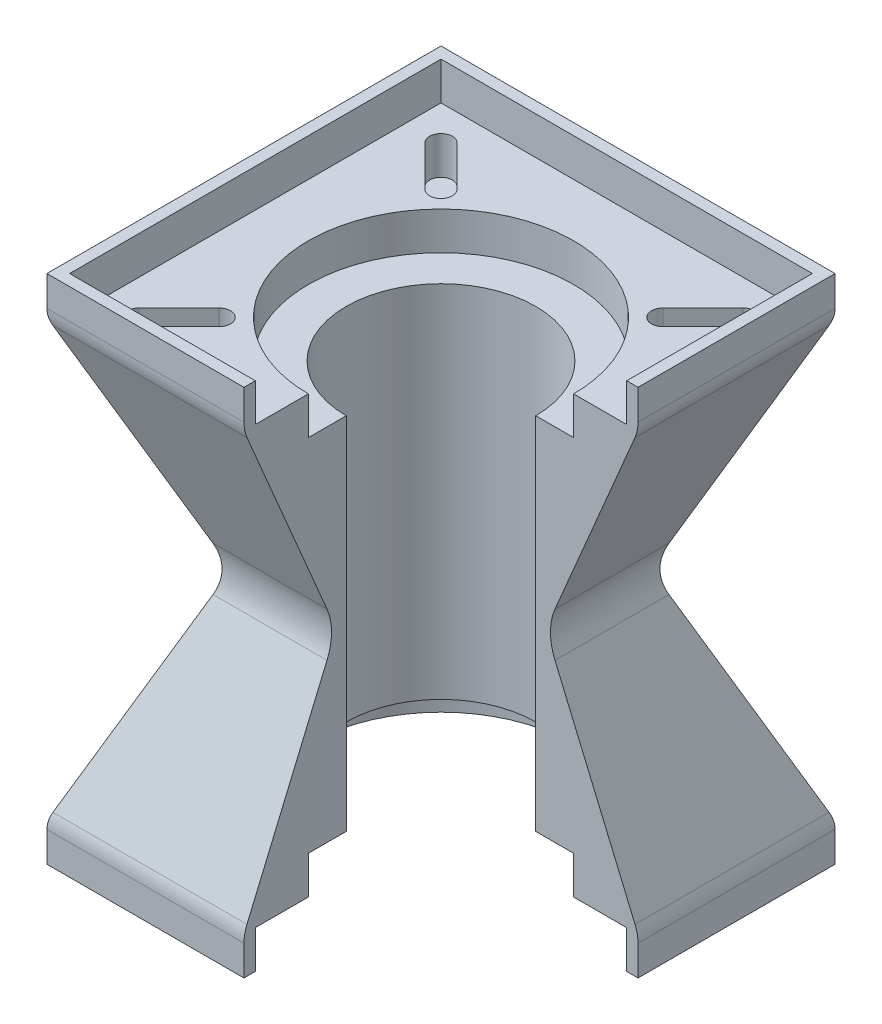
SolidWorks part; units mm, degrees
ref_plane "Front Plane" through (0, 0, 0) normal (0, 0, 1) x (1, 0, 0)
ref_plane "Top Plane" through (0, 0, 0) normal (0, 1, 0) x (1, 0, 0)
ref_plane "Right Plane" through (0, 0, 0) normal (1, 0, 0) x (0, 0, -1)
sketch "Sketch1" plane through (0, 0, 0) normal (0, 1, 0) x (1, 0, 0)
  line L1 (0, 0) -> (104, 0)
  line L2 (0, 0) -> (0, 104)
  line L3 (0, 104) -> (104, 104)
  line L4 (104, 0) -> (104, 104)
  dimension "D1" = 104
  dimension "D2" = 104
extrude "Boss-Extrude1" add sketch "Sketch1" along normal blind 115
sketch "Sketch2" plane through (0, 0, 0) normal (0, 0, 1) x (1, 0, 0)
  line L0 (0, 57.5) -> (104, 57.5) construction
  line L1 (0, 115) -> (0, 0) construction
  line L2 (104, 115) -> (104, 0) construction
  line L3 (104, 115) -> (79.5927, 57.5)
  line L4 (0, 115) -> (104, 115) construction
  line L5 (79.5927, 57.5) -> (104, 0)
  line L6 (0, 0) -> (104, 0) construction
  dimension "D1" = 23
extrude "Cut-Extrude1" cut sketch "Sketch2" against normal through all and the other way through all
sketch "Sketch3" plane through (0, 115, 0) normal (0, 1, 0) x (1, 0, 0)
  line L0 (0, 104) -> (104, 0) construction
  line L2 (0, 0) -> (104, 104) construction
  circle A0 centre (52, 52) radius 25
  dimension "D1" = 50
extrude "Cut-Extrude2" cut sketch "Sketch3" against normal through all
pattern_circular "CirPattern1" count 4 every 90 about axis through (52, 0, -52) along (0, 1, 0) of "Cut-Extrude2", "Cut-Extrude1"
sketch "Sketch4" plane through (0, 115, 0) normal (0, 1, 0) x (1, 0, 0)
  circle A0 centre (52, 52) radius 35
  dimension "D1" = 70
extrude "Cut-Extrude3" cut sketch "Sketch4" against normal blind 10
sketch "Sketch5" plane through (0, 0, 0) normal (0, -1, 0) x (1, 0, 0)
  circle A0 centre (52, -52) radius 35
  dimension "D1" = 70
extrude "Cut-Extrude4" cut sketch "Sketch5" against normal blind 10
fillet "Fillet2" radius 15 4 edges at (79.5927, 57.5, -52) (52, 57.5, -24.4073) (24.4073, 57.5, -52) (52, 57.5, -79.5927)
sketch "Sketch6" plane through (0, 115, 0) normal (0, 1, 0) x (1, 0, 0)
  line L4 (104, 104) -> (0, 104)
  line L5 (0, 104) -> (0, 0)
  line L6 (0, 0) -> (104, 0)
  line L7 (104, 0) -> (104, 104)
  line L8 (3, 101) -> (3, 3)
  line L9 (3, 3) -> (101, 3)
  line L10 (101, 3) -> (101, 101)
  line L11 (101, 101) -> (3, 101)
  line L12 (3, 101) -> (3, 3)
  line L13 (3, 3) -> (101, 3)
  line L14 (101, 3) -> (101, 101)
  line L15 (101, 101) -> (3, 101)
  dimension "D1" = 3
  dimension "D2" = 3
extrude "Boss-Extrude2" add sketch "Sketch6" along normal blind 10
sketch "Sketch7" plane through (0, 0, 0) normal (0, -1, 0) x (1, 0, 0)
  line L4 (104, 0) -> (0, 0)
  line L5 (0, 0) -> (0, -104)
  line L6 (0, -104) -> (104, -104)
  line L7 (104, -104) -> (104, 0)
  line L8 (3, -3) -> (3, -101)
  line L9 (3, -101) -> (101, -101)
  line L10 (101, -101) -> (101, -3)
  line L11 (101, -3) -> (3, -3)
  line L12 (3, -3) -> (3, -101)
  line L13 (3, -101) -> (101, -101)
  line L14 (101, -101) -> (101, -3)
  line L15 (101, -3) -> (3, -3)
  dimension "D1" = 3
  dimension "D2" = 3
extrude "Boss-Extrude3" add sketch "Sketch7" along normal blind 10
sketch "Sketch8" plane through (0, 0, 0) normal (0, -1, 0) x (1, 0, 0)
  line L0 (0, 0) -> (104, -104)
  line L1 (20.5337, -20.5337) -> (9.9271, -9.9271) construction
  line L4 (18.4124, -22.6551) -> (7.8058, -12.0485)
  line L5 (22.6551, -18.4124) -> (12.0485, -7.8058)
  line L6 (83.4663, -20.5337) -> (94.0729, -9.9271) construction
  line L7 (81.3449, -18.4124) -> (91.9515, -7.8058)
  line L8 (85.5876, -22.6551) -> (96.1942, -12.0485)
  line L9 (83.4663, -83.4663) -> (94.0729, -94.0729) construction
  line L10 (85.5876, -81.3449) -> (96.1942, -91.9515)
  line L11 (81.3449, -85.5876) -> (91.9515, -96.1942)
  line L12 (20.5337, -83.4663) -> (9.9271, -94.0729) construction
  line L13 (22.6551, -85.5876) -> (12.0485, -96.1942)
  line L14 (18.4124, -81.3449) -> (7.8058, -91.9515)
  arc A2 (18.4124, -22.6551) -> (22.6551, -18.4124) centre (20.5337, -20.5337) ccw
  arc A3 (12.0485, -7.8058) -> (7.8058, -12.0485) centre (9.9271, -9.9271) ccw
  circle A4 centre (52, -52) radius 52 construction
  arc A5 (81.3449, -18.4124) -> (85.5876, -22.6551) centre (83.4663, -20.5337) ccw
  arc A6 (96.1942, -12.0485) -> (91.9515, -7.8058) centre (94.0729, -9.9271) ccw
  arc A7 (85.5876, -81.3449) -> (81.3449, -85.5876) centre (83.4663, -83.4663) ccw
  arc A8 (91.9515, -96.1942) -> (96.1942, -91.9515) centre (94.0729, -94.0729) ccw
  arc A9 (22.6551, -85.5876) -> (18.4124, -81.3449) centre (20.5337, -83.4663) ccw
  arc A10 (7.8058, -91.9515) -> (12.0485, -96.1942) centre (9.9271, -94.0729) ccw
  point P6 (15.2304, -15.2304)
  point P18 (88.7696, -15.2304)
  point P25 (88.7696, -88.7696)
  point P32 (15.2304, -88.7696)
  point P37 (52, -52)
  dimension "D2" = 3
  dimension "D4" = 104
  dimension "D1" = 15
  dimension "D3" = 4
  dimension "D5" = 36.7696
extrude "Cut-Extrude8" cut sketch "Sketch8" against normal blind 10 contours L8 A6 L7 A5 | L14 A10 L13 A9 | L5 A3 L4 A2 | L11 A8 L10 A7
sketch "Sketch9" plane through (0, 115, 0) normal (0, 1, 0) x (1, 0, 0)
  line L0 (0, 0) -> (104, 104) construction
  line L1 (81.2633, 81.2633) -> (91.8699, 91.8699) construction
  line L2 (79.142, 83.3846) -> (89.7486, 93.9912)
  line L3 (83.3846, 79.142) -> (93.9912, 89.7486)
  line L4 (81.2633, 22.7367) -> (91.8699, 12.1301) construction
  line L5 (83.3846, 24.858) -> (93.9912, 14.2514)
  line L6 (79.142, 20.6154) -> (89.7486, 10.0088)
  line L7 (22.7367, 22.7367) -> (12.1301, 12.1301) construction
  line L8 (24.858, 20.6154) -> (14.2514, 10.0088)
  line L9 (20.6154, 24.858) -> (10.0088, 14.2514)
  line L10 (22.7367, 81.2633) -> (12.1301, 91.8699) construction
  line L11 (20.6154, 79.142) -> (10.0088, 89.7486)
  line L12 (24.858, 83.3846) -> (14.2514, 93.9912)
  arc A0 (79.142, 83.3846) -> (83.3846, 79.142) centre (81.2633, 81.2633) ccw
  arc A1 (93.9912, 89.7486) -> (89.7486, 93.9912) centre (91.8699, 91.8699) ccw
  arc A2 (83.3846, 24.858) -> (79.142, 20.6154) centre (81.2633, 22.7367) ccw
  arc A3 (89.7486, 10.0088) -> (93.9912, 14.2514) centre (91.8699, 12.1301) ccw
  arc A4 (24.858, 20.6154) -> (20.6154, 24.858) centre (22.7367, 22.7367) ccw
  arc A5 (10.0088, 14.2514) -> (14.2514, 10.0088) centre (12.1301, 12.1301) ccw
  arc A6 (20.6154, 79.142) -> (24.858, 83.3846) centre (22.7367, 81.2633) ccw
  arc A7 (14.2514, 93.9912) -> (10.0088, 89.7486) centre (12.1301, 91.8699) ccw
  point P6 (86.5666, 86.5666)
  point P11 (52, 52)
  point P17 (86.5666, 17.4334)
  point P24 (17.4334, 17.4334)
  point P31 (17.4334, 86.5666)
  point P36 (52, 52)
  dimension "D2" = 3
  dimension "D1" = 15
  dimension "D3" = 34.5666
  dimension "D4" = 4
extrude "Cut-Extrude9" cut sketch "Sketch9" against normal blind 10
fillet "Fillet3" radius 10 8 edges at (52, 0, -104) (104, 0, -52) (52, 0, 0) (0, 0, -52) (0, 115, -52) (52, 115, -104) (104, 115, -52) (52, 115, 0)
sketch "Sketch11" plane through (0, 125, 0) normal (0, 1, 0) x (1, 0, 0)
  line L1 (104, 0) -> (52, 0)
  line L2 (104, 0) -> (104, 52)
  line L3 (104, 52) -> (52, 52)
  line L4 (52, 0) -> (52, 52)
extrude "Cut-Extrude11" cut sketch "Sketch11" against normal through all
equation "\"a\"= 115"
equation "\"b\"= 104"
equation "\"c\"= 23"
